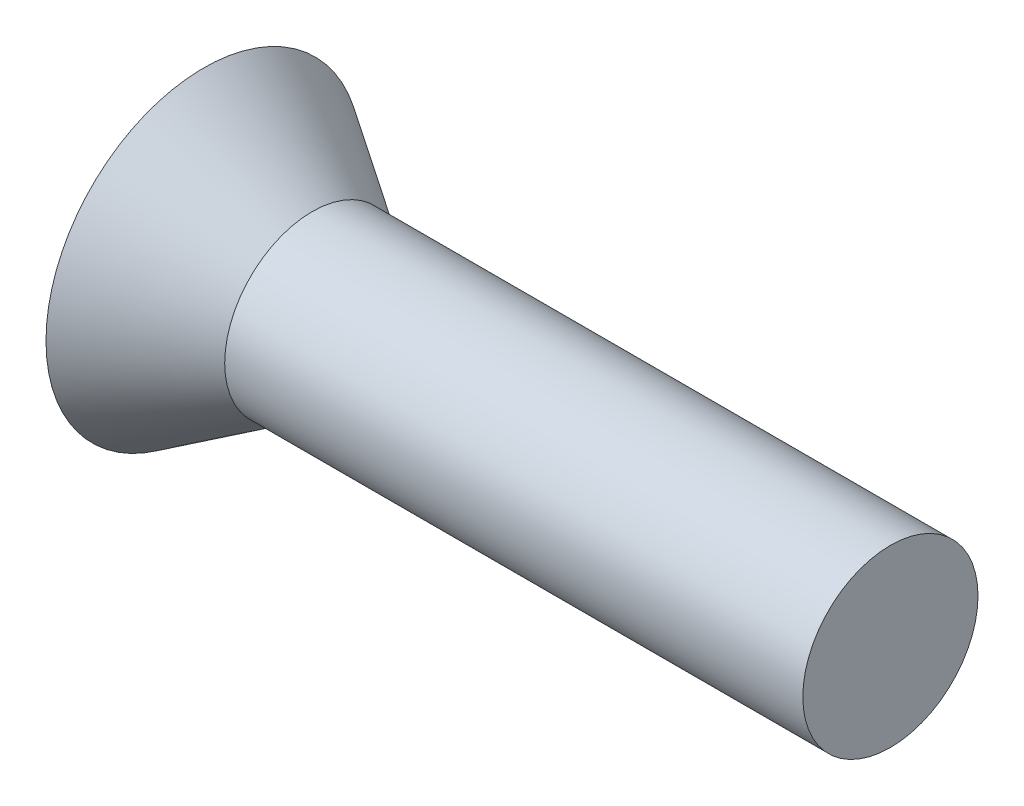
SolidWorks part; units mm, degrees
ref_plane "Front" through (0, 0, 0) normal (0, 0, 1) x (1, 0, 0)
ref_plane "Top" through (0, 0, 0) normal (0, 1, 0) x (1, 0, 0)
ref_plane "Right" through (0, 0, 0) normal (1, 0, 0) x (0, 0, -1)
sketch "Эскиз1" plane through (0, 0, 0) normal (0, 0, 1) x (1, 0, 0)
  line L0 (-51.6306, 0) -> (23.5345, 0) construction
  line L1 (-19.6, 0) -> (-19.6, 4.5)
  line L2 (-19.6, 4.5) -> (-16.5, 2.5)
  line L3 (-16.5, 2.5) -> (0, 2.5)
  line L4 (0, 2.5) -> (0, 0)
  line L5 (-19.6, 0) -> (0, 0)
  dimension "D1" = 19.6
  dimension "D2" = 2.5
  dimension "D3" = 4.5
  dimension "D4" = 16.5
revolve "Повернуть1" add sketch "Эскиз1" angle 360 about L0
sketch "Эскиз2" plane through (-19.6, 0, 0) normal (-1, 0, 0) x (0, 0, 1)
  line L1 (-0.5, 2.25) -> (0.5, 2.25)
  line L2 (-0.5, 2.25) -> (-0.5, -2.25)
  line L3 (-0.5, -2.25) -> (0.5, -2.25)
  line L4 (0.5, 2.25) -> (0.5, -2.25)
  line L5 (-0.5, 2.25) -> (0.5, -2.25) construction
  line L6 (-0.5, -2.25) -> (0.5, 2.25) construction
  line L7 (-2.25, 0.5) -> (2.25, 0.5)
  line L8 (-2.25, 0.5) -> (-2.25, -0.5)
  line L9 (-2.25, -0.5) -> (2.25, -0.5)
  line L10 (2.25, 0.5) -> (2.25, -0.5)
  line L11 (-2.25, 0.5) -> (2.25, -0.5) construction
  line L12 (-2.25, -0.5) -> (2.25, 0.5) construction
  point P0 (0, 0)
  point P6 (0, 0)
  dimension "D1" = 4.5
  dimension "D2" = 4.5
  dimension "D3" = 1
  dimension "D4" = 1
extrude "Вырез-Вытянуть1" cut sketch "Эскиз2" against normal blind 2 contours L2 L7 L4 L1 | L10 L7 L4 L9 | L9 L2 L3 L4 | L8 L9 L2 L7 | L2 L9 L4 L7
